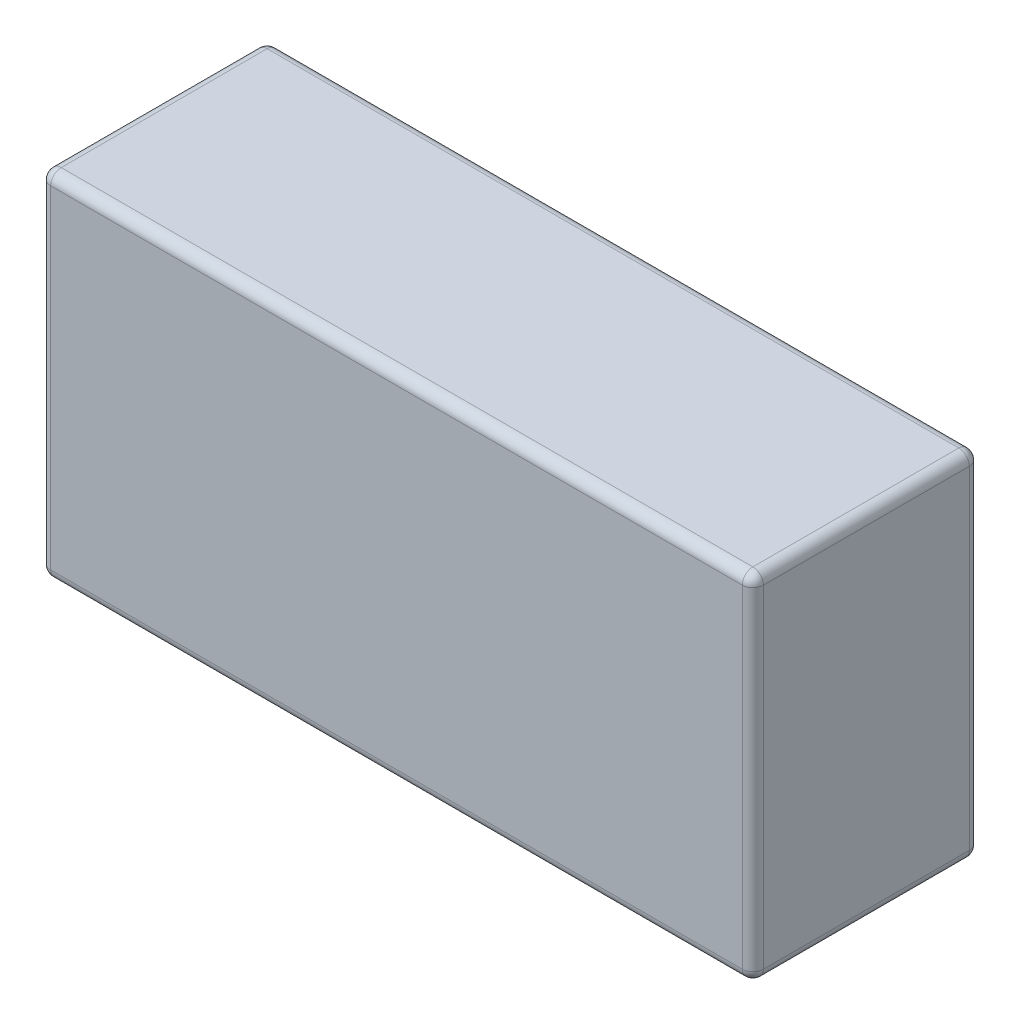
SolidWorks part; units mm, degrees
ref_plane "Спереди" through (0, 0, 0) normal (0, 0, 1) x (1, 0, 0)
ref_plane "Сверху" through (0, 0, 0) normal (0, 1, 0) x (1, 0, 0)
ref_plane "Справа" through (0, 0, 0) normal (1, 0, 0) x (0, 0, -1)
sketch "Эскиз1" plane through (0, 0, 0) normal (0, 1, 0) x (1, 0, 0)
  line L1 (0, 0) -> (-135, 0)
  line L2 (0, 0) -> (0, 43)
  line L3 (0, 43) -> (-135, 43)
  line L4 (-135, 0) -> (-135, 43)
  dimension "D1" = 135
  dimension "D2" = 43
extrude "Бобышка-Вытянуть1" add sketch "Эскиз1" along normal blind 67
fillet "Скругление1" radius 2 12 edges at (-135, 0, -21.5) (-135, 33.5, -43) (-67.5, 0, -43) (0, 33.5, -43) (0, 0, -21.5) (-135, 67, -21.5) (-67.5, 67, -43) (0, 67, -21.5) (-135, 33.5, 0) (-67.5, 67, 0) (0, 33.5, 0) (-67.5, 0, 0)
